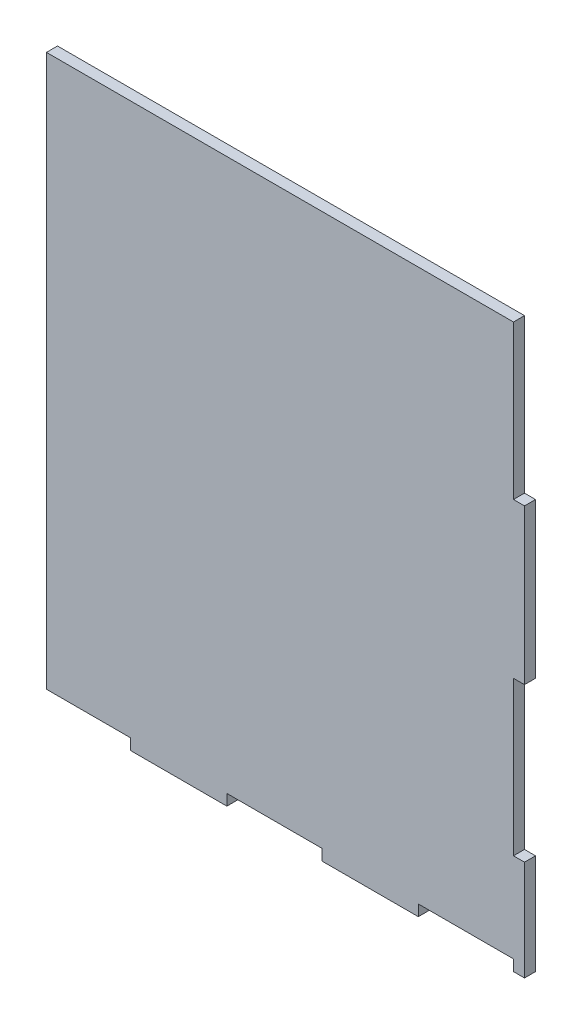
SolidWorks part; units mm, degrees
ref_plane "Front Plane" through (0, 0, 0) normal (0, 0, 1) x (1, 0, 0)
ref_plane "Top Plane" through (0, 0, 0) normal (0, 1, 0) x (1, 0, 0)
ref_plane "Right Plane" through (0, 0, 0) normal (1, 0, 0) x (0, 0, -1)
sketch "Sketch1" plane through (0, 0, 0) normal (0, 0, 1) x (1, 0, 0)
  line L0 (65.7414, 34.0484) -> (65.7414, -7.7588) construction
  line L1 (65.7414, -7.7588) -> (65.7414, -8.0588) construction
  line L2 (68.7414, -77.1445) -> (65.7414, -77.1445)
  line L4 (65.7414, -77.1445) -> (65.7414, -74.1445)
  line L5 (65.7414, -74.1445) -> (39.8614, -74.1445)
  line L6 (65.7414, 75.8555) -> (-64.2586, -74.1445) construction
  line L7 (65.7414, -74.1445) -> (-67.2586, 75.8555) construction
  line L8 (-61.2586, 75.8555) -> (-61.2586, -74.1445)
  line L10 (39.8614, -74.1445) -> (39.8614, -77.1445)
  line L11 (39.8614, -77.1445) -> (13.6814, -77.1445)
  line L12 (13.6814, -77.1445) -> (13.6814, -74.1445)
  line L13 (13.6814, -74.1445) -> (-12.1986, -74.1445)
  line L14 (-12.1986, -74.1445) -> (-12.1986, -77.1445)
  line L15 (-12.1986, -77.1445) -> (-38.3786, -77.1445)
  line L16 (-38.3786, -77.1445) -> (-38.3786, -74.1445)
  line L18 (13.6814, -74.1445) -> (39.5614, -74.1445) construction
  line L19 (39.5614, -74.1445) -> (39.8614, -74.1445) construction
  line L20 (-38.3786, -74.1445) -> (-64.2586, -74.1445)
  line L21 (-64.2586, 33.7484) -> (-61.2586, 33.7484) construction
  line L70 (65.7414, 75.8555) -> (65.7414, 34.0484)
  line L71 (65.7414, 34.0484) -> (68.7414, 34.0484)
  line L72 (68.7414, 34.0484) -> (68.7414, -8.0588)
  line L73 (68.7414, -8.0588) -> (65.7414, -8.0588)
  line L74 (65.7414, -8.0588) -> (65.7414, -49.8659)
  line L75 (65.7414, -49.8659) -> (68.7414, -49.8659)
  line L138 (68.7414, -77.1445) -> (68.7414, -49.8659)
  line L139 (65.7414, 75.8555) -> (-67.2586, 75.8555)
  line L140 (-67.2586, 75.8555) -> (-67.2586, 33.7484)
  line L141 (-67.2586, 33.7484) -> (-64.2586, 33.7484)
  line L142 (-64.2586, 33.7484) -> (-64.2586, -8.0588)
  line L143 (-64.2586, -8.0588) -> (-67.2586, -8.0588)
  line L144 (-67.2586, -8.0588) -> (-67.2586, -50.1659)
  line L145 (-67.2586, -50.1659) -> (-64.2586, -50.1659)
  line L146 (-64.2586, -74.1445) -> (-64.2586, -50.1659)
  dimension "D1" = 130
  dimension "D2" = 42.1071
  dimension "D3" = 0.3
  dimension "D4" = 3
  dimension "D5" = 150
  dimension "D6" = 0.3
extrude "Boss-Extrude1" add sketch "Sketch1" along normal blind 3 contours L70 L139 L8 L20 L16 L15 L14 L13 L12 L11 L10 L5 L4 L2 L138 L75 L74 L73 L72 L71
